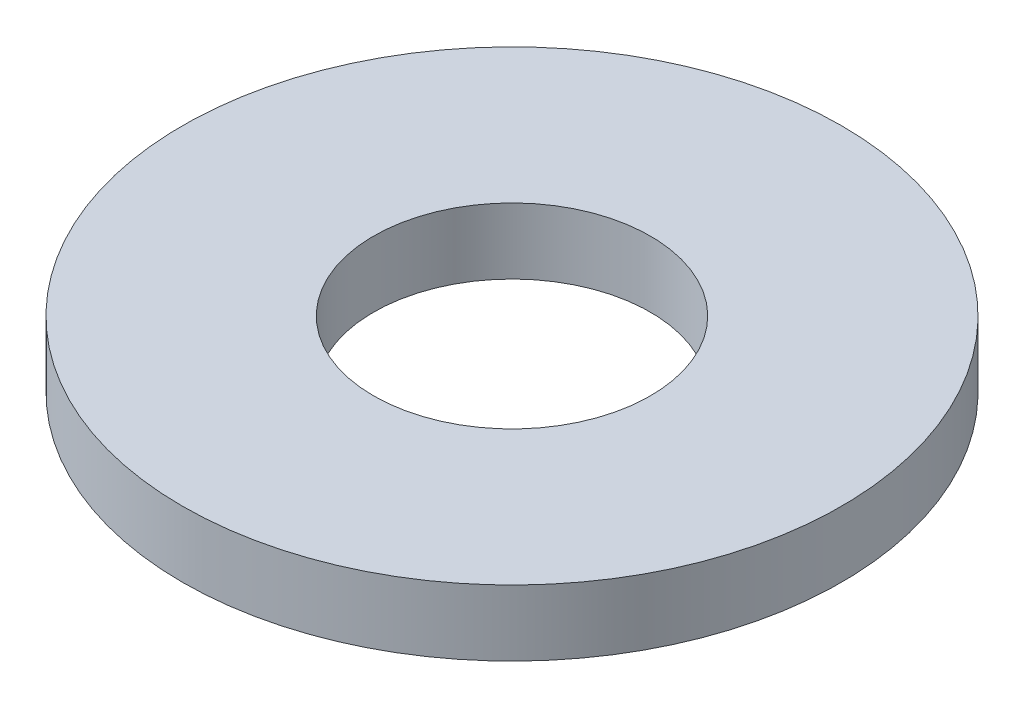
SolidWorks part; units mm, degrees
ref_plane "Alzado" through (0, 0, 0) normal (0, 0, 1) x (1, 0, 0)
ref_plane "Planta" through (0, 0, 0) normal (0, 1, 0) x (1, 0, 0)
ref_plane "Vista lateral" through (0, 0, 0) normal (1, 0, 0) x (0, 0, -1)
sketch "Croquis1" plane through (0, 0, 0) normal (0, 1, 0) x (1, 0, 0)
  circle A0 centre (0, 0) radius 5
  dimension "D1" = 10
extrude "Saliente-Extruir1" add sketch "Croquis1" along normal blind 1
sketch "Croquis2" plane through (0, 1, 0) normal (0, 1, 0) x (1, 0, 0)
  circle A0 centre (0, 0) radius 2.1
  dimension "D1" = 4.2
extrude "Cortar-Extruir1" cut sketch "Croquis2" against normal through all
